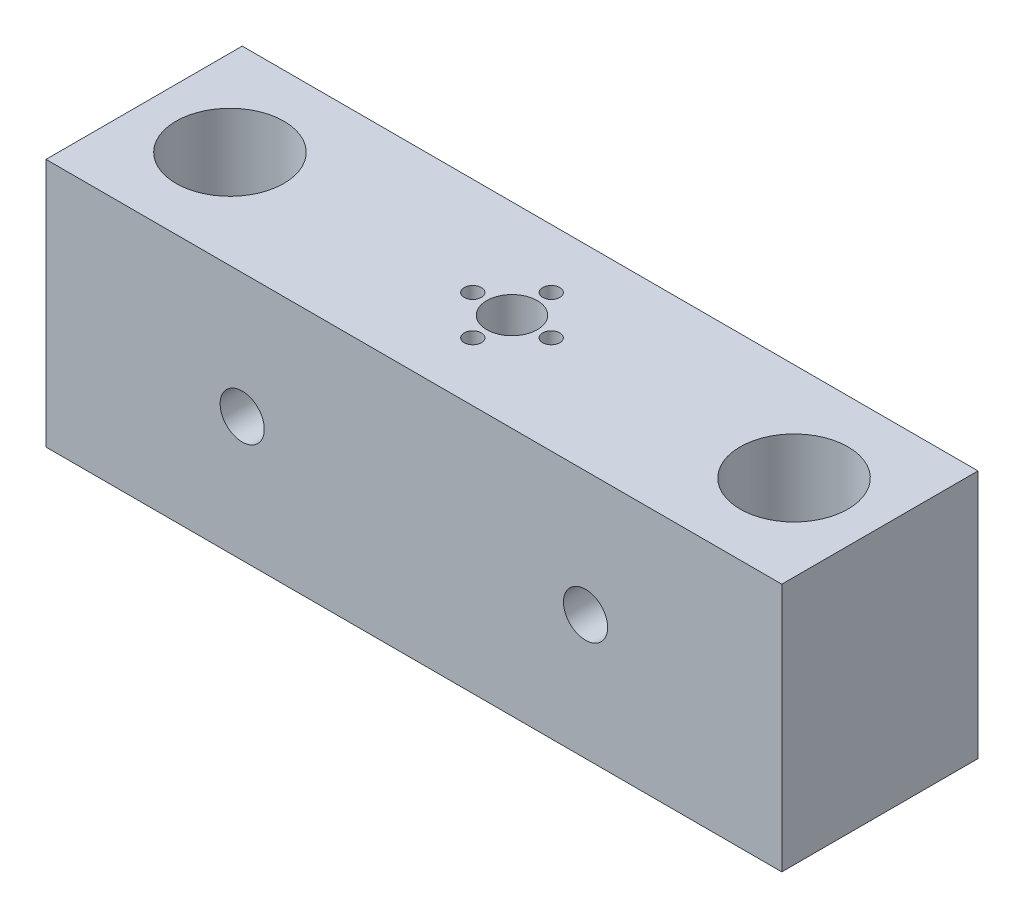
SolidWorks part; units mm, degrees
material "Liga 1060"
ref_plane "Frontal" through (0, 0, 0) normal (0, 0, 1) x (1, 0, 0)
ref_plane "Superior" through (0, 0, 0) normal (0, 1, 0) x (1, 0, 0)
ref_plane "Direito" through (0, 0, 0) normal (1, 0, 0) x (0, 0, -1)
sketch "Esboço1" plane through (0, 0, 0) normal (0, 1, 0) x (1, 0, 0)
  line L1 (-75, 20) -> (75, 20)
  line L2 (-75, 20) -> (-75, -20)
  line L3 (-75, -20) -> (75, -20)
  line L4 (75, 20) -> (75, -20)
  line L5 (-75, 20) -> (75, -20) construction
  line L6 (-75, -20) -> (75, 20) construction
  point P0 (0, 0)
  dimension "D1" = 150
  dimension "D2" = 40
extrude "Ressalto-extrusão1" add sketch "Esboço1" along normal blind 50.8
sketch "Esboço2" plane through (0, 50.8, 0) normal (0, 1, 0) x (1, 0, 0)
  line L0 (-75, 20) -> (-75, -20) construction
  line L2 (75, 20) -> (-75, 20) construction
  line L3 (75, -20) -> (75, 20) construction
  circle A0 centre (0, 0) radius 5.15
  circle A1 centre (-57.5, 0) radius 11
  circle A2 centre (57.5, 0) radius 11
  dimension "D1" = 22
  dimension "D2" = 22
  dimension "D3" = 10.3
  dimension "D4" = 17.5
  dimension "D5" = 17.5
  dimension "D6" = 20
  dimension "D7" = 20
extrude "Corte-extrusão1" cut sketch "Esboço2" along normal through all and the other way through all
sketch "Esboço3" plane through (0, 50.8, 0) normal (0, 1, 0) x (1, 0, 0)
  circle A0 centre (0, 0) radius 8
  circle A1 centre (0, 8) radius 1.75
  dimension "D1" = 3.5
extrude "Corte-extrusão2" cut sketch "Esboço3" against normal through all contours A0 A1 | A0 A1
pattern_circular "PadrãoCircular1" count 4 over 360 about axis through (0, 0, 0) along (0, 1, 0) of "Corte-extrusão2"
sketch "Esboço5" plane through (0, 0, -20) normal (0, 0, -1) x (-1, 0, 0)
  line L1 (75, 50.8) -> (75, 0) construction
  line L2 (-75, 50.8) -> (-75, 0) construction
  line L4 (-75, 25.4) -> (75, 25.4) construction
  circle A0 centre (35, 25.4) radius 4
  circle A1 centre (-35, 25.4) radius 4
  dimension "D3" = 8
  dimension "D1" = 40
  dimension "D2" = 40
extrude "Corte-extrusão3" cut sketch "Esboço5" against normal through all
hole_wizard "Furo roscado de M10x1.01" positions "Esboço10" profile "Esboço11" tap size "M10x1.0" standard "ISO" end condition through all
sketch "Esboço10" plane through (0, 0, -20) normal (0, 0, -1) x (-1, 0, 0)
  point P0 (35, 25.4)
  point P3 (-35, 25.4)
sketch "Esboço11" plane through (-35, 25.4, -20) normal (1, 0, 0) x (0, 1, 0)
  line L0 (0, 0) -> (0, 40)
  line L1 (0, 40) -> (4.5, 40)
  line L2 (4.5, 40) -> (4.5, 0.525)
  line L3 (4.5, 0.525) -> (5.025, 0)
  line L5 (5.025, 0) -> (0, 0)
  line L6 (-4.5, 0.525) -> (-5.025, 0) construction
  line L11 (0, -6.35) -> (0, 107.95) construction
  dimension "Thru Tap Drill Dia." = 9
  dimension "Thru Tap Drill Depth" = 40
  dimension "Near C'Sink Dia." = 10.05
  dimension "Near C'Sink Angle" = 90
cosmetic thread "Rosca de furo1" parameters "D2"=10
cosmetic thread "Rosca de furo2" parameters "D2"=10
